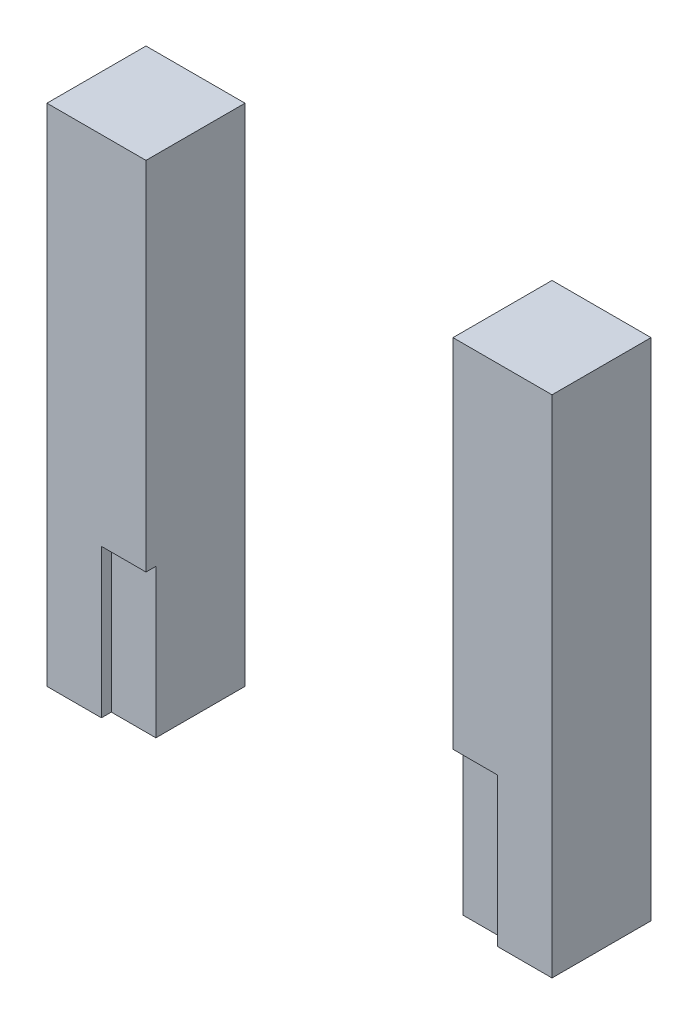
SolidWorks part; units mm, degrees
ref_plane "Front Plane" through (0, 0, 0) normal (0, 0, 1) x (1, 0, 0)
ref_plane "Top Plane" through (0, 0, 0) normal (0, 1, 0) x (1, 0, 0)
ref_plane "Right Plane" through (0, 0, 0) normal (1, 0, 0) x (0, 0, -1)
sketch "Sketch1" plane through (0, 0, 0) normal (0, 0, 1) x (1, 0, 0)
  line L1 (-155, 155) -> (155, 155)
  line L2 (-155, 155) -> (-155, -155)
  line L3 (-155, -155) -> (155, -155)
  line L4 (155, 155) -> (155, -155)
  line L5 (-155, 155) -> (155, -155) construction
  line L6 (-155, -155) -> (155, 155) construction
  line L7 (-255, 255) -> (255, 255)
  line L8 (-255, 255) -> (-255, -255)
  line L9 (-255, -255) -> (255, -255)
  line L10 (255, 255) -> (255, -255)
  line L11 (-255, 255) -> (255, -255) construction
  line L12 (-255, -255) -> (255, 255) construction
  point P0 (0, 0)
  point P6 (0, 0)
  dimension "D1" = 310
  dimension "D2" = 510
extrude "Boss-Extrude1" add sketch "Sketch1" along normal mid plane 100
sketch "Sketch2" plane through (0, 0, 50) normal (0, 0, 1) x (1, 0, 0)
  line L0 (-255, -255) -> (255, -255) construction
  line L1 (-200, -105) -> (200, -105)
  line L2 (-200, -105) -> (-200, -255)
  line L3 (-200, -255) -> (200, -255)
  line L4 (200, -105) -> (200, -255)
  line L5 (-200, -105) -> (200, -255) construction
  line L6 (-200, -255) -> (200, -105) construction
  point P0 (0, -180)
  dimension "D1" = 400
  dimension "D2" = 150
extrude "Cut-Extrude1" cut sketch "Sketch2" against normal blind 10
sketch "Sketch3" plane through (0, 0, -50) normal (0, 0, -1) x (-1, 0, 0)
  line L6 (-155, -155) -> (155, -155)
  line L7 (155, 155) -> (155, 255)
  line L8 (-255, 255) -> (255, 255) construction
  line L9 (155, 255) -> (-155, 255)
  line L10 (-155, 255) -> (-155, 155)
  line L11 (-155, 155) -> (155, 155)
  line L12 (-155, -155) -> (-155, -255)
  line L13 (255, -255) -> (-255, -255) construction
  line L14 (-155, -255) -> (155, -255)
  line L15 (155, -255) -> (155, -155)
extrude "Cut-Extrude2" cut sketch "Sketch3" against normal through all
